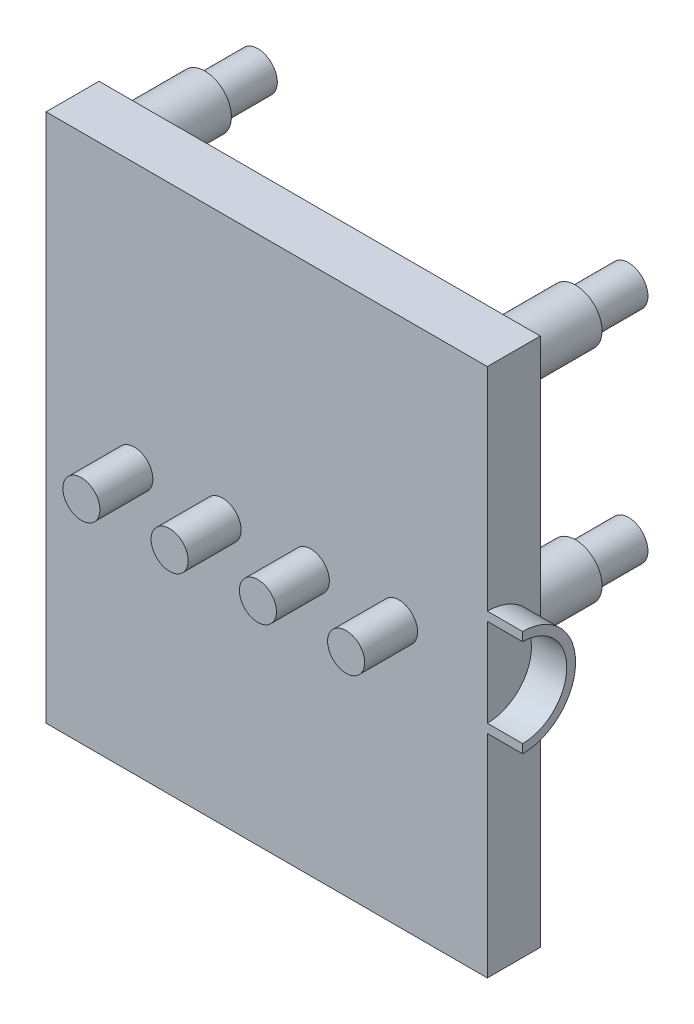
SolidWorks part; units mm, degrees
material "PA Tipo 6"
ref_plane "Alzado" through (0, 0, 0) normal (0, 0, 1) x (1, 0, 0)
ref_plane "Planta" through (0, 0, 0) normal (0, 1, 0) x (1, 0, 0)
ref_plane "Vista lateral" through (0, 0, 0) normal (1, 0, 0) x (0, 0, -1)
sketch "Croquis1" plane through (0, 0, 0) normal (0, 0, 1) x (1, 0, 0)
  line L1 (-12.5, -15) -> (12.5, -15)
  line L2 (-12.5, -15) -> (-12.5, 15)
  line L3 (-12.5, 15) -> (12.5, 15)
  line L4 (12.5, -15) -> (12.5, 15)
  line L5 (-12.5, -15) -> (12.5, 15) construction
  line L6 (-12.5, 15) -> (12.5, -15) construction
  point P0 (0, 0)
  dimension "D1" = 25
  dimension "D2" = 30
extrude "Saliente-Extruir1" add sketch "Croquis1" along normal blind 3
sketch "Croquis2" plane through (0, 0, 3) normal (0, 0, 1) x (1, 0, 0)
  line L0 (-12.5, 15) -> (-12.5, -15) construction
  line L1 (12.5, -15) -> (12.5, 15) construction
  circle A0 centre (-7.5, 0) radius 1.05
  circle A1 centre (-2.5, 0) radius 1.05
  circle A2 centre (2.5, 0) radius 1.05
  circle A3 centre (7.5, 0) radius 1.05
  dimension "D5" = 2.1
  dimension "D1" = 5
  dimension "D2" = 5
  dimension "D3" = 5
  dimension "D4" = 5
extrude "Saliente-Extruir2" add sketch "Croquis2" along normal blind 3
sketch "Croquis3" plane through (12.5, 0, 0) normal (1, 0, 0) x (0, 0, -1)
  line L0 (-3, 1.05) -> (-3, -1.05) construction
  line L5 (-3, -2.5) -> (-3, 2.5) construction
  line L6 (-3, 3) -> (-3, 2.5)
  line L7 (-3, -2.5) -> (-3, -3)
  line L8 (-3.5, -2.958) -> (-3.5, 2.958) construction
  arc A0 (-3, -2.5) -> (-3, 2.5) centre (-3, 0) ccw
  arc A2 (-3, -3) -> (-3, 3) centre (-3, 0) ccw
  arc A3 (-3.5, -2.958) -> (-3.5, 2.958) centre (-3, 0) ccw construction
  dimension "D1" = 5
  dimension "D2" = 0.5
extrude "Saliente-Extruir3" add sketch "Croquis3" along normal blind 2
sketch "Croquis4" plane through (0, 0, 0) normal (0, 0, -1) x (-1, 0, 0)
  circle A0 centre (10.5, 13) radius 1.5
  circle A1 centre (-10.5, 13) radius 1.5
  circle A2 centre (-10.5, 0.5) radius 1.5
  circle A3 centre (10.5, 0.5) radius 1.5
  dimension "D1" = 3
  dimension "D2" = 13
  dimension "D3" = 21
  dimension "D4" = 10.5
  dimension "D5" = 12.5
extrude "Saliente-Extruir4" add sketch "Croquis4" along normal blind 4
sketch "Croquis5" plane through (0, 0, -4) normal (0, 0, -1) x (-1, 0, 0)
  circle A0 centre (10.5, 13) radius 1.1
  circle A1 centre (-10.5, 13) radius 1.1
  circle A2 centre (-10.5, 0.5) radius 1.1
  circle A3 centre (10.5, 0.5) radius 1.1
  dimension "D1" = 2.2
extrude "Saliente-Extruir5" add sketch "Croquis5" along normal blind 3
